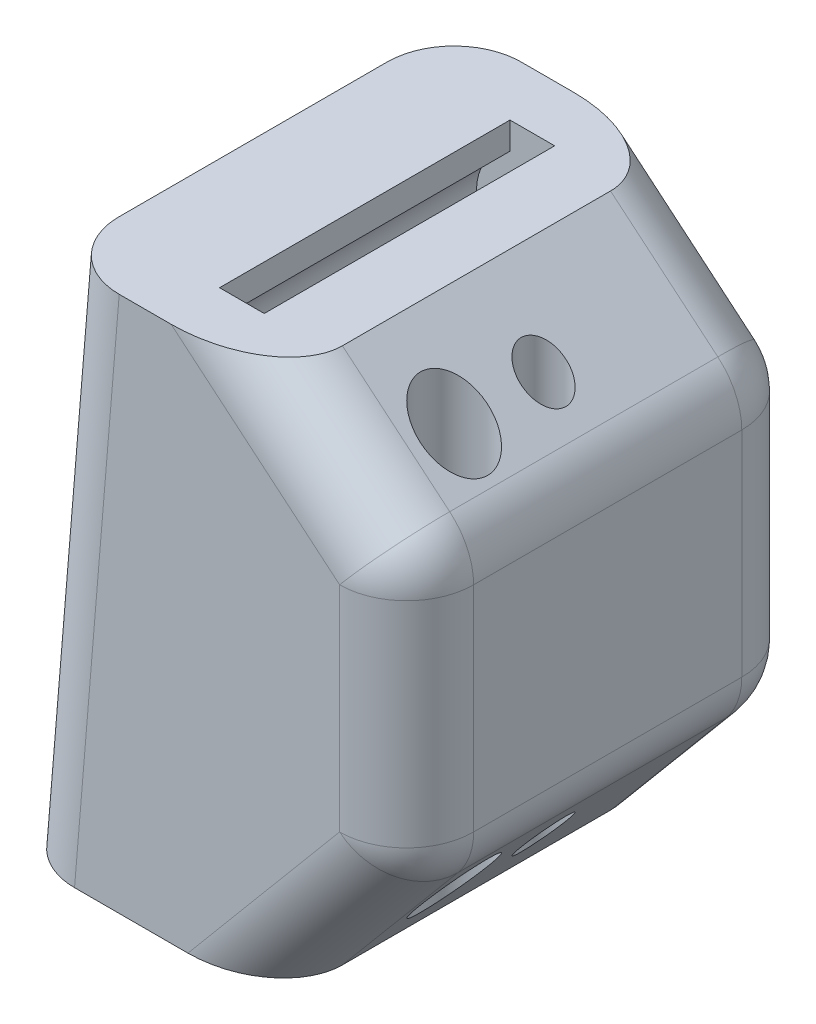
SolidWorks part; units mm, degrees
ref_plane "Front Plane" through (0, 0, 0) normal (0, 0, 1) x (1, 0, 0)
ref_plane "Top Plane" through (0, 0, 0) normal (0, 1, 0) x (1, 0, 0)
ref_plane "Right Plane" through (0, 0, 0) normal (1, 0, 0) x (0, 0, -1)
sketch "Sketch2" plane through (0, 0, 0) normal (0, 0, 1) x (1, 0, 0)
  line L0 (0, 0) -> (12, 0)
  line L1 (12, 0) -> (17.1718, 6.1635)
  line L2 (0, 0) -> (2, 24)
  line L3 (2, 24) -> (12, 24)
  line L4 (12, 24) -> (16.8021, 19.9706)
  line L5 (17.8737, 17.6725) -> (17.8737, 8.0919)
  arc A0 (16.8021, 19.9706) -> (17.8737, 17.6725) centre (14.8737, 17.6725) cw
  arc A1 (17.1718, 6.1635) -> (17.8737, 8.0919) centre (14.8737, 8.0919) ccw
  point P9 (17.8737, 19.0714)
  point P12 (17.8737, 7)
  dimension "D8" = 3
  dimension "D9" = 3
  dimension "D1" = 12
  dimension "D2" = 130
  dimension "D3" = 7
  dimension "D4" = 2
  dimension "D5" = 24
  dimension "D6" = 10
  dimension "D7" = 140
extrude "Boss-Extrude1" add sketch "Sketch2" along normal blind 18
sketch "Sketch3" plane through (0, 0, 18) normal (0, 0, 1) x (1, 0, 0)
  line L0 (12, 24) -> (2, 24) construction
  line L2 (7, 24) -> (9, 24)
  line L3 (7, 24) -> (7, 22.7913)
  line L5 (9, 24) -> (9, 22.7913)
  arc A0 (7, 22.7913) -> (9, 22.7913) centre (8, 20.5) ccw
  point P0 (8, 24)
  dimension "D2" = 5
  dimension "D1" = 8
  dimension "D3" = 3.5
  dimension "D4" = 2
  dimension "D5" = 1
extrude "Cut-Extrude1" cut sketch "Sketch3" against normal blind 13 from offset 2.5 offset against normal yes
sketch "Sketch4" plane through (0, 0, 0) normal (0, 0, -1) x (-1, 0, 0)
  line L0 (0, 0) -> (-12, 0) construction
  line L2 (-9, 0) -> (-7, 0)
  line L3 (-9, 0) -> (-9, 1.2087)
  line L5 (-7, 0) -> (-7, 1.2087)
  arc A0 (-7, 1.2087) -> (-9, 1.2087) centre (-8, 3.5) ccw
  point P0 (-8, 0)
  dimension "D2" = 5
  dimension "D1" = 8
  dimension "D3" = 3.5
  dimension "D4" = 2
  dimension "D5" = 1
extrude "Cut-Extrude2" cut sketch "Sketch4" against normal blind 13 from offset 2.5 offset against normal yes
sketch "Sketch5" plane through (0, 0, 0) normal (0, 1, 0) x (1, 0, 0)
  line L0 (12, -18) -> (12, 0) construction
  circle A0 centre (15, -9) radius 1
  circle A1 centre (15, -13) radius 1.5
  point P0 (12, -9)
  dimension "D1" = 2
  dimension "D4" = 3
  dimension "D2" = 3
  dimension "D3" = 15
  dimension "D5" = 4
extrude "Cut-Extrude3" cut sketch "Sketch5" along normal blind 25
fillet "Fillet1" radius 3 12 edges at (14.5859, 3.0818, 0) (17.6928, 7.0659, 0) (14.401, 21.9853, 0) (17.5926, 18.9403, 0) (14.5859, 3.0818, 18) (17.6928, 7.0659, 18) (14.401, 21.9853, 18) (17.5926, 18.9403, 18) (1, 12, 0) (17.8737, 12.8822, 0) (1, 12, 18) (17.8737, 12.8822, 18)
ref_plane "Plane1" through (0, 0, 9) normal (0, 0, 1) x (1, 0, 0)
